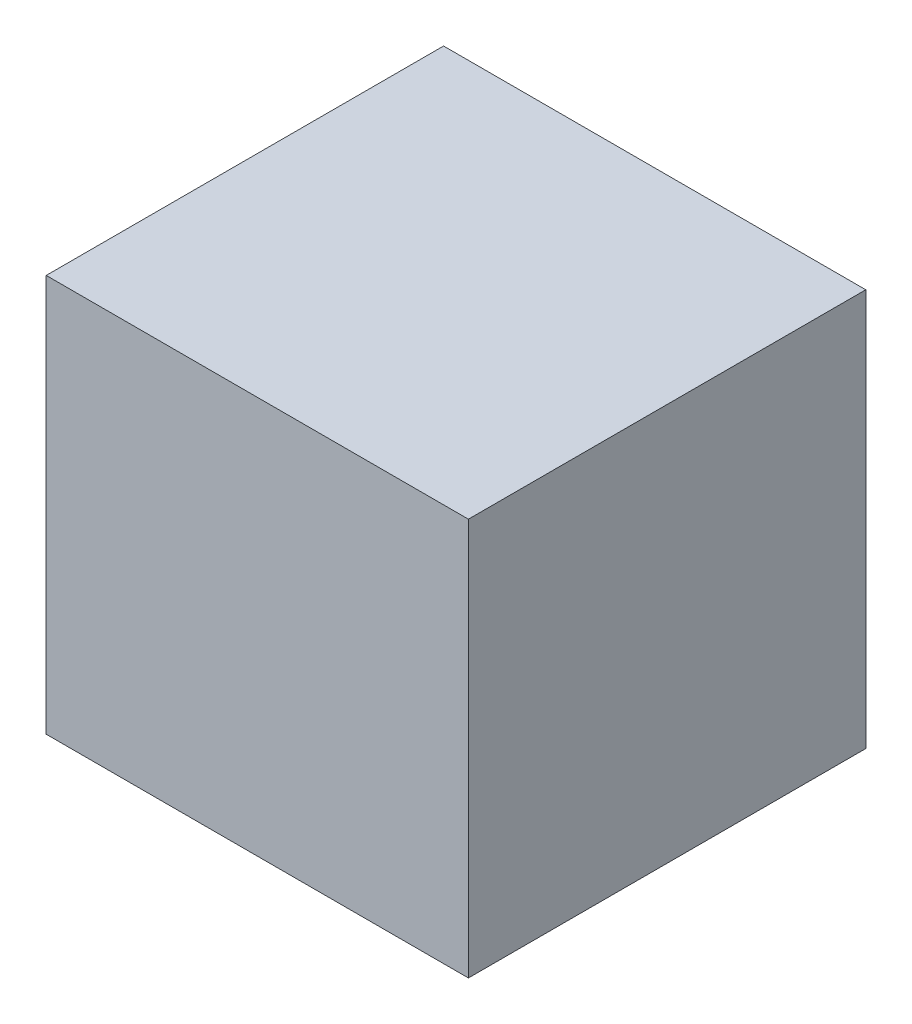
SolidWorks part; units mm, degrees
material "ABS"
ref_plane "Front Plane" through (0, 0, 0) normal (0, 0, 1) x (1, 0, 0)
ref_plane "Top Plane" through (0, 0, 0) normal (0, 1, 0) x (1, 0, 0)
ref_plane "Right Plane" through (0, 0, 0) normal (1, 0, 0) x (0, 0, -1)
sketch "Sketch1" plane through (0, 0, 0) normal (1, 0, 0) x (0, 0, -1)
  line L1 (-16, 52) -> (16, 52)
  line L2 (-16, 52) -> (-16, 84)
  line L3 (-16, 84) -> (16, 84)
  line L4 (16, 52) -> (16, 84)
extrude "Boss-Extrude1" add sketch "Sketch1" along normal mid plane 34 from offset 39
sketch "Sketch2" plane through (0, 0, 0) normal (1, 0, 0) x (0, 0, -1)
  line L1 (-6.7, 61.8) -> (6.7, 61.8)
  line L2 (-6.7, 61.8) -> (-6.7, 74.2)
  line L3 (-6.7, 74.2) -> (6.7, 74.2)
  line L4 (6.7, 61.8) -> (6.7, 74.2)
extrude "Cut-Extrude1" cut sketch "Sketch2" against normal mid plane 10 from offset 27
sketch "Sketch3" plane through (0, 0, 0) normal (1, 0, 0) x (0, 0, -1)
  line L1 (-6.7, 58.8) -> (6.7, 58.8)
  line L2 (-6.7, 58.8) -> (-6.7, 77.2)
  line L3 (-6.7, 77.2) -> (6.7, 77.2)
  line L4 (6.7, 58.8) -> (6.7, 77.2)
extrude "Cut-Extrude2" cut sketch "Sketch3" against normal mid plane 4.4 from offset 34.2
